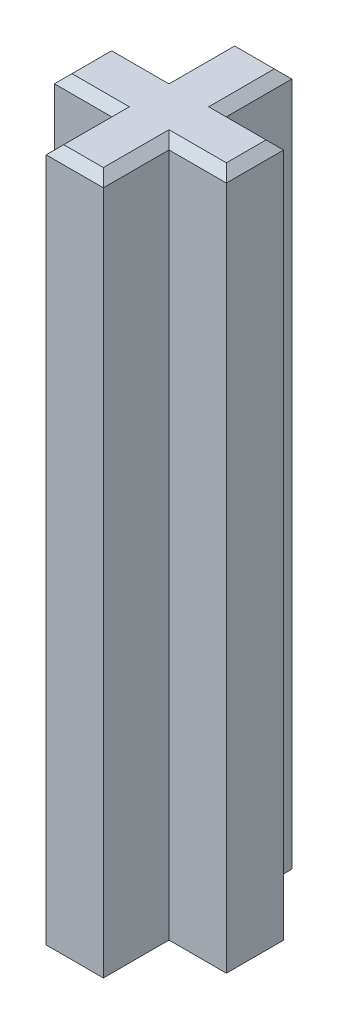
SolidWorks part; units mm, degrees
ref_plane "Front Plane" through (0, 0, 0) normal (0, 0, 1) x (1, 0, 0)
ref_plane "Top Plane" through (0, 0, 0) normal (0, 1, 0) x (1, 0, 0)
ref_plane "Right Plane" through (0, 0, 0) normal (1, 0, 0) x (0, 0, -1)
sketch "Sketch1" plane through (0, 0, 0) normal (0, 1, 0) x (1, 0, 0)
  line L0 (0, 2.685) -> (-7.7254, 2.685) construction
  line L1 (0, 0) -> (1.63, 0)
  line L2 (0, 0) -> (0, 5.37)
  line L3 (0, 5.37) -> (1.63, 5.37)
  line L4 (1.63, 0) -> (1.63, 5.37)
  line L5 (-7.7254, 2.685) -> (-7.7254, 3.5) construction
  line L7 (-1.635, 3.5) -> (3.265, 3.5)
  line L8 (-1.635, 3.5) -> (-1.635, 1.87)
  line L9 (-1.635, 1.87) -> (3.265, 1.87)
  line L10 (3.265, 3.5) -> (3.265, 1.87)
  point P12 (0, 0)
  point P13 (0, 0)
  point P14 (0, 0)
  dimension "D1" = 5.37
  dimension "D2" = 1.63
  dimension "D3" = 0.815
  dimension "D4" = 1.63
  dimension "D5" = 4.9
  dimension "D6" = 1.635
  dimension "D7" = 1.635
  dimension "D8" = 1.87
  dimension "D9" = 1.87
extrude "Boss-Extrude1" add sketch "Sketch1" along normal blind 20 contours L8 L9 L2 L7 | L2 L9 L4 L7 | L2 L7 L4 L3 | L10 L7 L4 L9 | L9 L2 L1 L4
chamfer "Chamfer1" distance 0.25 angle 45 12 edges at (-0.8175, 20, -3.5) (0, 20, -4.435) (0.815, 20, -5.37) (1.63, 20, -4.435) (2.4475, 20, -3.5) (3.265, 20, -2.685) (2.4475, 20, -1.87) (1.63, 20, -0.935) (0.815, 20, 0) (0, 20, -0.935) (-0.8175, 20, -1.87) (-1.635, 20, -2.685)
chamfer "Chamfer2" distance 0.25 angle 45 12 edges at (-0.8175, 0, -1.87) (0, 0, -0.935) (0.815, 0, 0) (1.63, 0, -0.935) (2.4475, 0, -1.87) (3.265, 0, -2.685) (2.4475, 0, -3.5) (1.63, 0, -4.435) (0.815, 0, -5.37) (0, 0, -4.435) (-0.8175, 0, -3.5) (-1.635, 0, -2.685)
